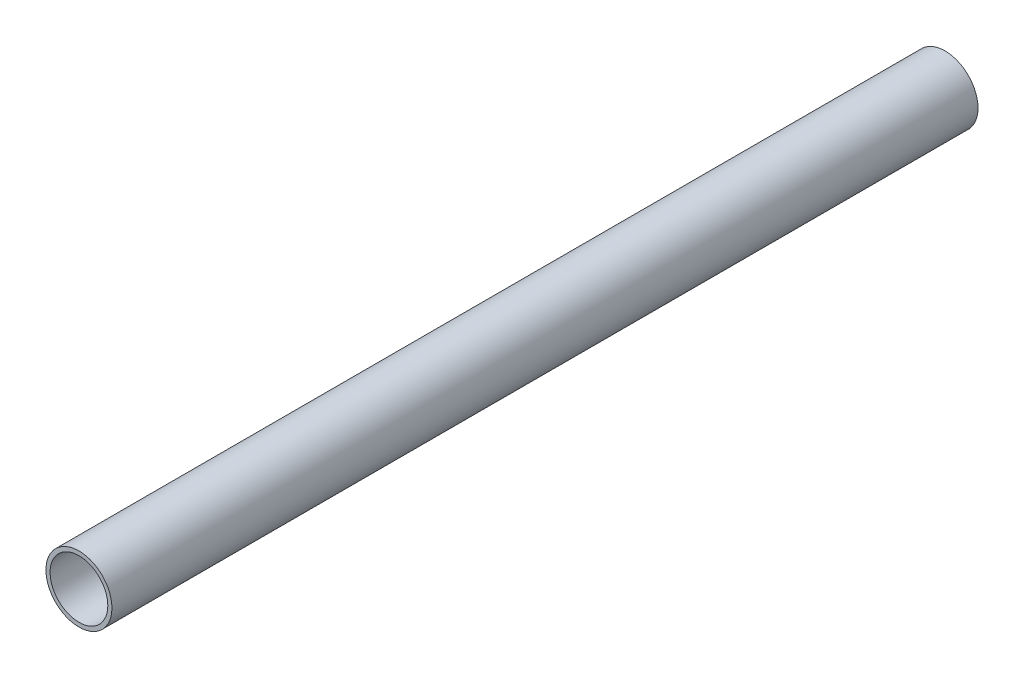
SolidWorks part; units mm, degrees
material "Thornel Mat VMA"
ref_plane "前视基准面" through (0, 0, 0) normal (0, 0, 1) x (1, 0, 0)
ref_plane "上视基准面" through (0, 0, 0) normal (0, 1, 0) x (1, 0, 0)
ref_plane "右视基准面" through (0, 0, 0) normal (1, 0, 0) x (0, 0, -1)
sketch "草图1" plane through (0, 0, 0) normal (0, 0, 1) x (1, 0, 0)
  circle A0 centre (0, 0) radius 4
  circle A1 centre (0, 0) radius 3.5
  dimension "D1" = 8
  dimension "D2" = 0.5
extrude "凸台-拉伸1" add sketch "草图1" along normal blind 105
